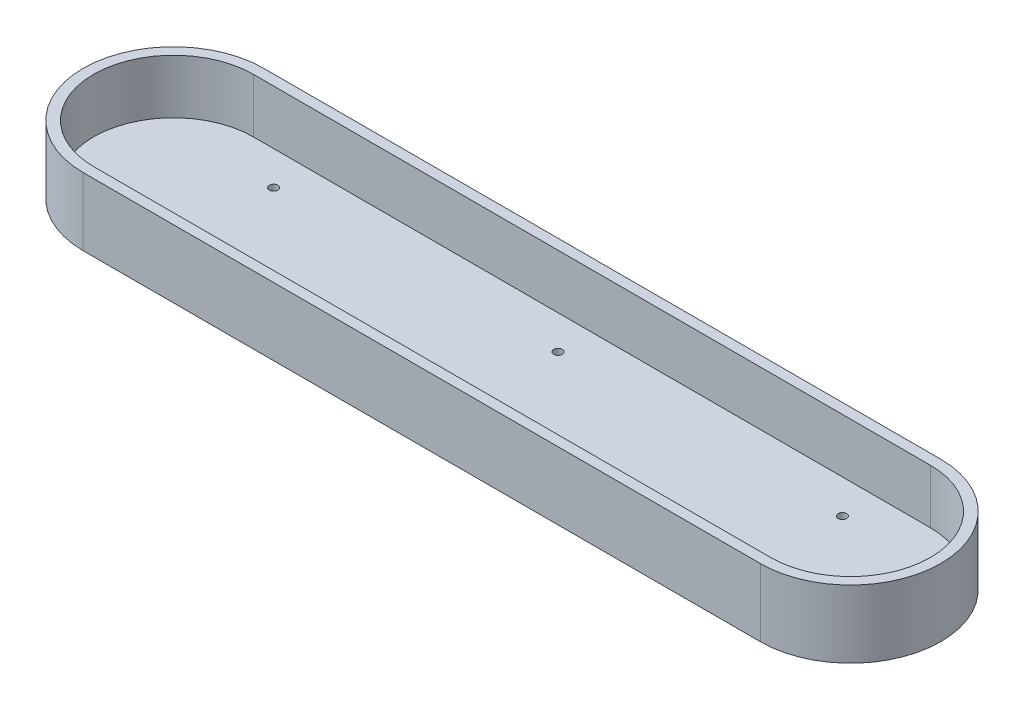
SolidWorks part; units mm, degrees
ref_plane "Front Plane" through (0, 0, 0) normal (0, 0, 1) x (1, 0, 0)
ref_plane "Top Plane" through (0, 0, 0) normal (0, 1, 0) x (1, 0, 0)
ref_plane "Right Plane" through (0, 0, 0) normal (1, 0, 0) x (0, 0, -1)
sketch "Sketch1" plane through (0, 0, 0) normal (0, 1, 0) x (1, 0, 0)
  line L0 (-95.25, 0) -> (95.25, 0) construction
  line L1 (0, -55.9739) -> (0, 55.9739) construction
  line L2 (-95.25, 22.479) -> (95.25, 22.479)
  line L3 (-95.25, -22.479) -> (95.25, -22.479)
  arc A0 (-95.25, 22.479) -> (-95.25, -22.479) centre (-95.25, 0) ccw
  arc A1 (95.25, 22.479) -> (95.25, -22.479) centre (95.25, 0) cw
  point P4 (0, 0)
  point P10 (0, 0)
  dimension "D2" = 44.958
  dimension "D1" = 190.5
extrude "MainBlock" add sketch "Sketch1" along normal blind 3.81
sketch "Sketch2" plane through (0, 0, 0) normal (0, -1, 0) x (1, 0, 0)
  line L0 (0, 0) -> (0, 50000) construction
  line L1 (-95.25, 25.4) -> (95.25, 25.4)
  line L2 (-95.25, -22.479) -> (95.25, -22.479)
  line L3 (95.25, 22.479) -> (-95.25, 22.479)
  line L5 (95.25, 22.479) -> (-95.25, 22.479)
  line L6 (-95.25, 0) -> (49904.75, 0) construction
  line L7 (95.25, -22.479) -> (-95.25, -22.479)
  line L8 (-95.25, -25.4) -> (95.25, -25.4)
  arc A0 (-95.25, 25.4) -> (-95.25, -25.4) centre (-95.25, 0) ccw
  arc A1 (95.25, 22.479) -> (95.25, -22.479) centre (95.25, 0) cw
  arc A2 (-95.25, 22.479) -> (-95.25, -22.479) centre (-95.25, 0) ccw
  arc A3 (95.25, -22.479) -> (95.25, 22.479) centre (95.25, 0) ccw
  arc A4 (-95.25, 22.479) -> (-95.25, -22.479) centre (-95.25, 0) ccw
  arc A6 (95.25, 25.4) -> (95.25, -25.4) centre (95.25, 0) cw
  point P0 (0, 22.479)
  point P15 (0, 25.4)
  point P16 (0, -22.479)
  point P19 (0, -25.4)
  dimension "2.1" = 50.8
  dimension "D1" = 0
extrude "Boss-Extrude1" add sketch "Sketch2" against normal blind 19.05
sketch "Sketch3" plane through (0, 0, 0) normal (0, -1, 0) x (1, 0, 0)
  line L0 (0, 0) -> (50000, 0) construction
  line L1 (0, 0) -> (0, 50000) construction
  line L2 (-95.25, 0.9216) -> (-95.25, 50000.9216) construction
  arc A0 (-95.25, 25.4) -> (-95.25, -25.4) centre (-95.25, 0) ccw construction
  arc A1 (-95.25, 25.4) -> (-95.25, -25.4) centre (-95.25, 0) ccw construction
  circle A2 centre (0, 12.954) radius 1.2065
  circle A3 centre (-80.01, 12.954) radius 1.2065
  circle A4 centre (80.01, 12.954) radius 1.2065
  circle A5 centre (80.01, -12.954) radius 1.2065
  circle A6 centre (-80.01, -12.954) radius 1.2065
  circle A7 centre (0, -12.954) radius 1.2065
  dimension "D1" = 2.413
  dimension "D4" = 2.413
  dimension "D2" = 12.954
  dimension "D3" = 12.954
  dimension "D5" = 15.24
extrude "Cut-Extrude1" cut sketch "Sketch3" against normal through all
equation "\"D4@Sketch3\"=\"D1@Sketch3\""
